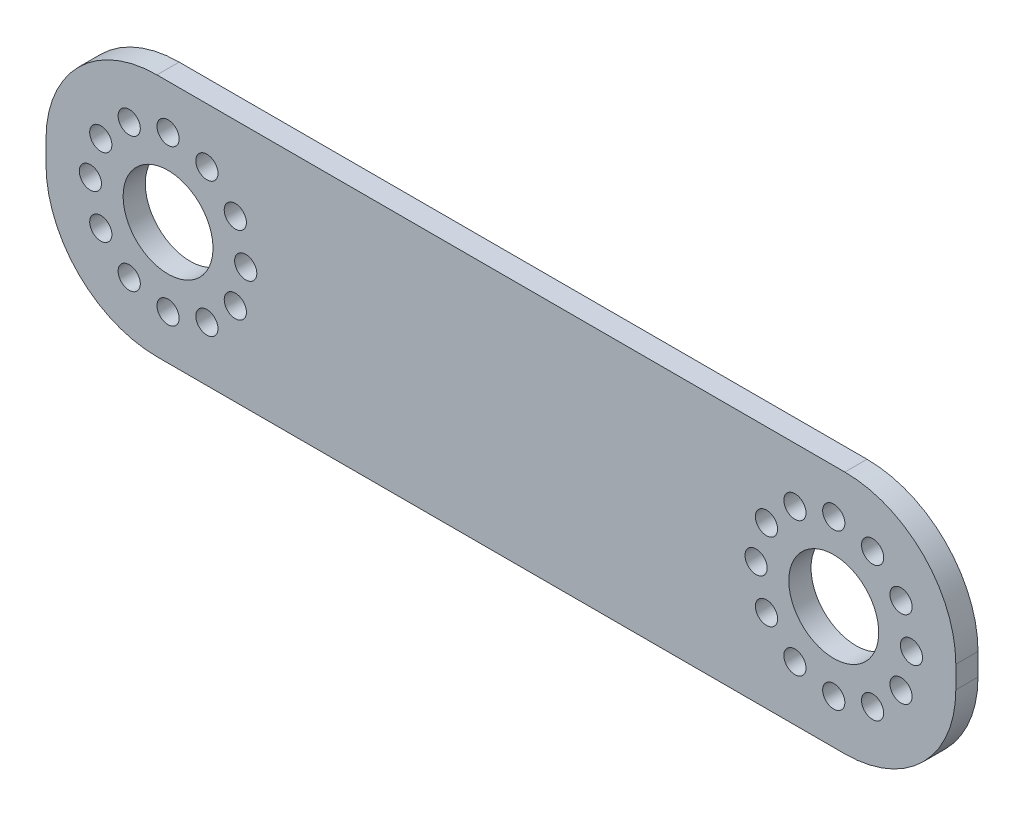
SolidWorks part; units mm, degrees
ref_plane "Plan de face" through (0, 0, 0) normal (0, 0, 1) x (1, 0, 0)
ref_plane "Plan de dessus" through (0, 0, 0) normal (0, 1, 0) x (1, 0, 0)
ref_plane "Plan de droite" through (0, 0, 0) normal (1, 0, 0) x (0, 0, -1)
sketch "Esquisse2" plane through (0, 0, 0) normal (0, 0, -1) x (-1, 0, 0)
  line L0 (-82, -11) -> (0, -11)
  line L2 (0, -11) -> (0, 11)
  line L3 (0, 11) -> (-82, 11)
  line L4 (-82, 11) -> (-82, -11)
  line L5 (-95.5557, 0) -> (0, 0) construction
  point P2 (0, 0)
  point P3 (0, 0)
  point P4 (-93.6063, 2.3966)
  point P14 (0, 0)
  point P15 (0, 0)
  point P16 (0, 0)
  point P17 (0, 0)
  circle B0 centre (-11, 0) radius 4.05
  circle B1 centre (-4, 0) radius 1
  circle B2 centre (-4.9378, -3.5) radius 1
  circle B3 centre (-7.5, -6.0622) radius 1
  circle B4 centre (-11, -7) radius 1
  circle B5 centre (-14.5, -6.0622) radius 1
  circle B6 centre (-17.0622, -3.5) radius 1
  circle B7 centre (-18, 0) radius 1
  circle B8 centre (-17.0622, 3.5) radius 1
  circle B9 centre (-14.5, 6.0622) radius 1
  circle B10 centre (-11, 7) radius 1
  circle B11 centre (-7.5, 6.0622) radius 1
  circle B12 centre (-4.9378, 3.5) radius 1
  circle B13 centre (-71, 0) radius 4.05
  circle B14 centre (-64, 0) radius 1
  circle B15 centre (-64.9378, -3.5) radius 1
  circle B16 centre (-67.5, -6.0622) radius 1
  circle B17 centre (-71, -7) radius 1
  circle B18 centre (-74.5, -6.0622) radius 1
  circle B19 centre (-77.0622, -3.5) radius 1
  circle B20 centre (-78, 0) radius 1
  circle B21 centre (-77.0622, 3.5) radius 1
  circle B22 centre (-74.5, 6.0622) radius 1
  circle B23 centre (-71, 7) radius 1
  circle B24 centre (-67.5, 6.0622) radius 1
  circle B25 centre (-64.9378, 3.5) radius 1
  dimension "D1" = 22
  dimension "D2" = 11
  dimension "D3" = 11
  dimension "D4" = 60
sketch_block_instance "Block1-1"
sketch_block "Block1" parameters "D2"=2, "D3"=8.1, "D1"=7
sketch_block_instance "Block1-2"
extrude "Boss.-Extru.1" add sketch "Esquisse2" against normal blind 2
fillet "Congé1" radius 10 4 edges at (0, -11, 1) (0, 11, 1) (82, 11, 1) (82, -11, 1)
